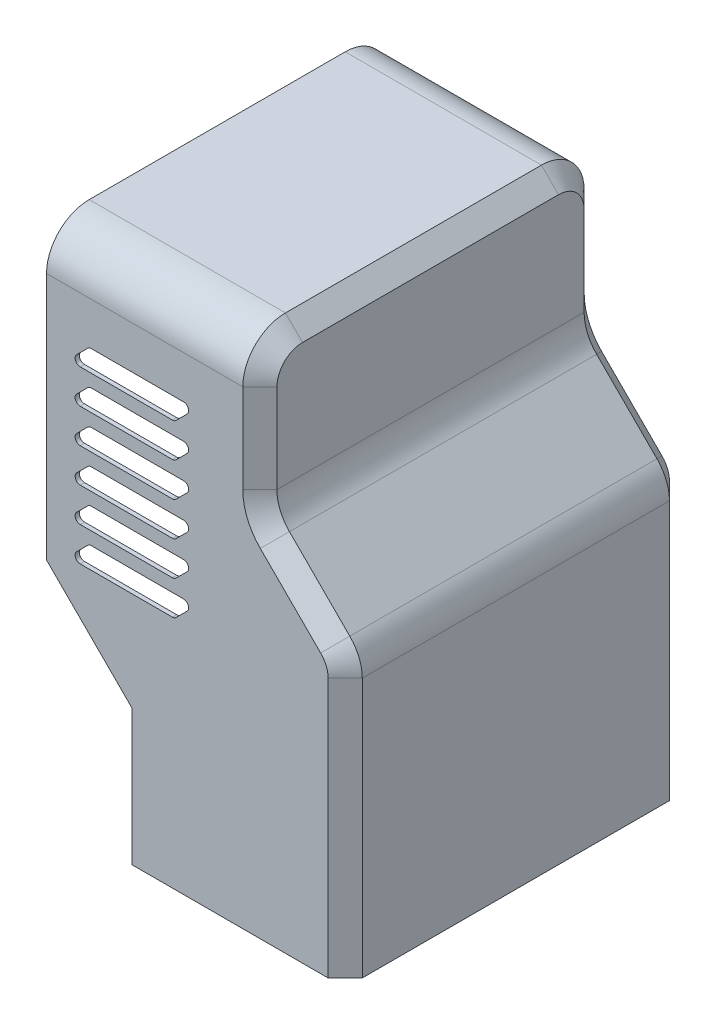
SolidWorks part; units mm, degrees
ref_plane "Front Plane" through (0, 0, 0) normal (0, 0, 1) x (1, 0, 0)
ref_plane "Top Plane" through (0, 0, 0) normal (0, 1, 0) x (1, 0, 0)
ref_plane "Right Plane" through (0, 0, 0) normal (1, 0, 0) x (0, 0, -1)
sketch "Sketch1" plane through (0, 0, 0) normal (0, 0, 1) x (1, 0, 0)
  line L0 (0, 0) -> (2500, 0)
  line L1 (2500, 0) -> (2500, 3250)
  line L2 (2500, 3250) -> (1500, 4250)
  line L3 (1500, 4250) -> (1500, 6000)
  line L4 (1500, 6000) -> (-1000, 6000)
  line L5 (-1000, 6000) -> (-1000, 2591.6876)
  line L6 (-1000, 2591.6876) -> (0, 1591.6876)
  line L7 (0, 1591.6876) -> (0, 0)
  point P8 (2654.321, 1635.8025)
  point P10 (1604.9383, 2947.5309)
  point P11 (2500, 1342.5926)
  dimension "D1" = 2500
  dimension "D2" = 2500
  dimension "D3" = 6000
  dimension "D4" = 45
  dimension "D5" = 2750
  dimension "D6" = 1750
  dimension "D7" = 3000
extrude "Boss-Extrude1" add sketch "Sketch1" along normal mid plane 4000
fillet "Fillet1" radius 500 4 edges at (2500, 3250, 0) (1500, 4250, 0) (250, 6000, -2000) (250, 6000, 2000)
chamfer "Chamfer1" distance 200 angle 45 13 edges at (2500, 1521.4466, 2000) (2500, 1521.4466, -2000) (2461.9398, 3234.2349, 2000) (2461.9398, 3234.2349, -2000) (2000, 3750, 2000) (2000, 3750, -2000) (1538.0602, 4265.7651, 2000) (1538.0602, 4265.7651, -2000) (1500, 4978.5534, 2000) (1500, 4978.5534, -2000) (1500, 5853.5534, 1853.5534) (1500, 5853.5534, -1853.5534) (1500, 6000, 0)
shell "Shell1" thickness 50
sketch "Sketch2" plane through (0, 0, 0) normal (0, 0, 1) x (1, 0, 0)
  line L4 (-517.5736, 4982.4264) -> (-647.5736, 4852.4264)
  line L5 (-475.1472, 5000) -> (605.1472, 5000)
  line L6 (-605.1472, 4750) -> (475.1472, 4750)
  line L7 (647.5736, 4897.5736) -> (517.5736, 4767.5736)
  line L9 (-1000, 6000) -> (-1000, 5500) construction
  line L10 (-1000, 6000) -> (1300, 6000) construction
  line L11 (-517.5736, 4582.4264) -> (-647.5736, 4452.4264)
  line L12 (-475.1472, 4600) -> (605.1472, 4600)
  line L13 (647.5736, 4497.5736) -> (517.5736, 4367.5736)
  line L14 (-605.1472, 4350) -> (475.1472, 4350)
  line L15 (-517.5736, 4182.4264) -> (-647.5736, 4052.4264)
  line L16 (-475.1472, 4200) -> (605.1472, 4200)
  line L17 (647.5736, 4097.5736) -> (517.5736, 3967.5736)
  line L18 (-605.1472, 3950) -> (475.1472, 3950)
  line L19 (-517.5736, 3782.4264) -> (-647.5736, 3652.4264)
  line L20 (-475.1472, 3800) -> (605.1472, 3800)
  line L21 (647.5736, 3697.5736) -> (517.5736, 3567.5736)
  line L22 (-605.1472, 3550) -> (475.1472, 3550)
  line L23 (-517.5736, 3382.4264) -> (-647.5736, 3252.4264)
  line L24 (-475.1472, 3400) -> (605.1472, 3400)
  line L25 (647.5736, 3297.5736) -> (517.5736, 3167.5736)
  line L26 (-605.1472, 3150) -> (475.1472, 3150)
  line L27 (-517.5736, 2982.4264) -> (-647.5736, 2852.4264)
  line L28 (-475.1472, 3000) -> (605.1472, 3000)
  line L29 (647.5736, 2897.5736) -> (517.5736, 2767.5736)
  line L30 (-605.1472, 2750) -> (475.1472, 2750)
  arc A0 (475.1472, 4750) -> (517.5736, 4767.5736) centre (475.1472, 4810) ccw
  arc A1 (605.1472, 5000) -> (647.5736, 4897.5736) centre (605.1472, 4940) cw
  arc A2 (-475.1472, 5000) -> (-517.5736, 4982.4264) centre (-475.1472, 4940) ccw
  arc A3 (-647.5736, 4852.4264) -> (-605.1472, 4750) centre (-605.1472, 4810) ccw
  arc A4 (-647.5736, 4452.4264) -> (-605.1472, 4350) centre (-605.1472, 4410) ccw
  arc A5 (-475.1472, 4600) -> (-517.5736, 4582.4264) centre (-475.1472, 4540) ccw
  arc A6 (605.1472, 4600) -> (647.5736, 4497.5736) centre (605.1472, 4540) cw
  arc A7 (475.1472, 4350) -> (517.5736, 4367.5736) centre (475.1472, 4410) ccw
  arc A8 (-647.5736, 4052.4264) -> (-605.1472, 3950) centre (-605.1472, 4010) ccw
  arc A9 (-475.1472, 4200) -> (-517.5736, 4182.4264) centre (-475.1472, 4140) ccw
  arc A10 (605.1472, 4200) -> (647.5736, 4097.5736) centre (605.1472, 4140) cw
  arc A11 (475.1472, 3950) -> (517.5736, 3967.5736) centre (475.1472, 4010) ccw
  arc A12 (-647.5736, 3652.4264) -> (-605.1472, 3550) centre (-605.1472, 3610) ccw
  arc A13 (-475.1472, 3800) -> (-517.5736, 3782.4264) centre (-475.1472, 3740) ccw
  arc A14 (605.1472, 3800) -> (647.5736, 3697.5736) centre (605.1472, 3740) cw
  arc A15 (475.1472, 3550) -> (517.5736, 3567.5736) centre (475.1472, 3610) ccw
  arc A16 (-647.5736, 3252.4264) -> (-605.1472, 3150) centre (-605.1472, 3210) ccw
  arc A17 (-475.1472, 3400) -> (-517.5736, 3382.4264) centre (-475.1472, 3340) ccw
  arc A18 (605.1472, 3400) -> (647.5736, 3297.5736) centre (605.1472, 3340) cw
  arc A19 (475.1472, 3150) -> (517.5736, 3167.5736) centre (475.1472, 3210) ccw
  arc A20 (-647.5736, 2852.4264) -> (-605.1472, 2750) centre (-605.1472, 2810) ccw
  arc A21 (-475.1472, 3000) -> (-517.5736, 2982.4264) centre (-475.1472, 2940) ccw
  arc A22 (605.1472, 3000) -> (647.5736, 2897.5736) centre (605.1472, 2940) cw
  arc A23 (475.1472, 2750) -> (517.5736, 2767.5736) centre (475.1472, 2810) ccw
  point P12 (750, 5000)
  point P15 (-500, 5000)
  point P18 (-750, 4750)
  dimension "D6" = 60
  dimension "D1" = 250
  dimension "D2" = 1000
  dimension "D3" = 1500
  dimension "D4" = 45
  dimension "D5" = 250
  dimension "D7" = 6
extrude "Cut-Extrude1" cut sketch "Sketch2" against normal through all both and the other way through all
